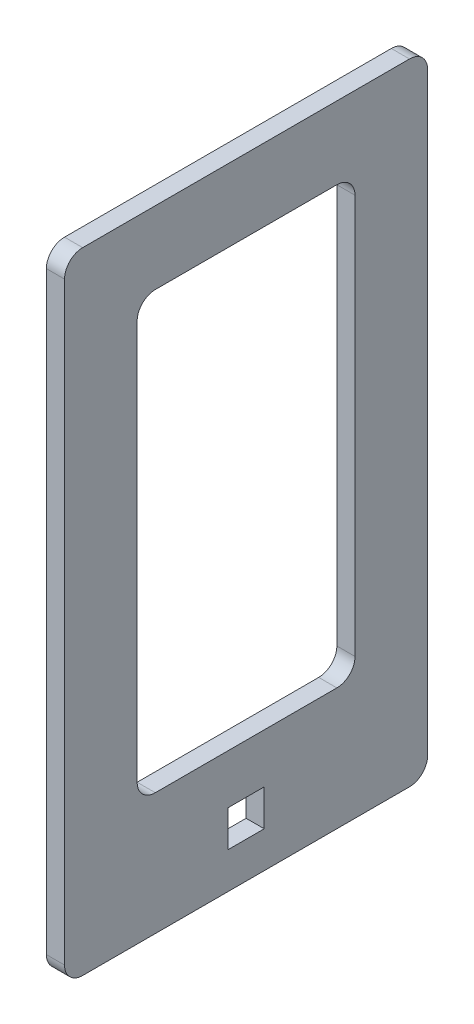
SolidWorks part; units mm, degrees
material "Balsa"
ref_plane "Front Plane" through (0, 0, 0) normal (0, 0, 1) x (1, 0, 0)
ref_plane "Top Plane" through (0, 0, 0) normal (0, 1, 0) x (1, 0, 0)
ref_plane "Right Plane" through (0, 0, 0) normal (1, 0, 0) x (0, 0, -1)
sketch "Sketch3" plane through (0, 0, 0) normal (1, 0, 0) x (0, 0, -1)
  line L0 (-31.75, -67.564) -> (31.75, -67.564)
  line L1 (-57.15, -110.236) -> (57.15, -110.236)
  line L2 (-63.5, -103.886) -> (-63.5, 103.886)
  line L3 (-57.15, 110.236) -> (57.15, 110.236)
  line L4 (63.5, -103.886) -> (63.5, 103.886)
  line L5 (-63.5, -110.236) -> (63.5, 110.236) construction
  line L6 (-63.5, 110.236) -> (63.5, -110.236) construction
  line L8 (-38.1, -61.214) -> (-38.1, 78.486)
  line L9 (-31.75, 84.836) -> (31.75, 84.836)
  line L11 (0, 0) -> (38.1, 84.836) construction
  line L12 (-38.1, 84.836) -> (0, 0) construction
  line L13 (38.1, -61.214) -> (38.1, 78.486)
  arc A0 (-57.15, -110.236) -> (-63.5, -103.886) centre (-57.15, -103.886) cw
  arc A1 (63.5, -103.886) -> (57.15, -110.236) centre (57.15, -103.886) cw
  arc A2 (63.5, 103.886) -> (57.15, 110.236) centre (57.15, 103.886) ccw
  arc A3 (-63.5, 103.886) -> (-57.15, 110.236) centre (-57.15, 103.886) cw
  arc A4 (31.75, -67.564) -> (38.1, -61.214) centre (31.75, -61.214) ccw
  arc A5 (-31.75, -67.564) -> (-38.1, -61.214) centre (-31.75, -61.214) cw
  arc A6 (31.75, 84.836) -> (38.1, 78.486) centre (31.75, 78.486) cw
  arc A7 (-38.1, 78.486) -> (-31.75, 84.836) centre (-31.75, 78.486) cw
  point P0 (0, 0)
  point P6 (0, 0)
  point P26 (38.1, -67.564)
  dimension "D7" = 6.35
  dimension "D8" = 6.35
  dimension "D1" = 220.472
  dimension "D2" = 127
  dimension "D3" = 76.2
  dimension "D4" = 152.4
  dimension "D5" = 25.4
  dimension "D6" = 25.4
extrude "Boss-Extrude2" add sketch "Sketch3" along normal blind 6.35
sketch "Sketch4" plane through (6.35, 0, 0) normal (1, 0, 0) x (0, 0, -1)
  line L0 (0, 3.4925) -> (0, -3.4925) construction
  line L1 (-6.35, -97.536) -> (6.35, -97.536)
  line L2 (-6.35, -97.536) -> (-6.35, -84.836)
  line L3 (-6.35, -84.836) -> (6.35, -84.836)
  line L4 (6.35, -97.536) -> (6.35, -84.836)
  line L5 (-6.35, -97.536) -> (6.35, -84.836) construction
  line L6 (-6.35, -84.836) -> (6.35, -97.536) construction
  line L7 (-57.15, -110.236) -> (57.15, -110.236) construction
  point P0 (0, -91.186)
  dimension "D1" = 12.7
  dimension "D2" = 12.7
  dimension "D3" = 12.7
extrude "Cut-Extrude1" cut sketch "Sketch4" against normal up to next
